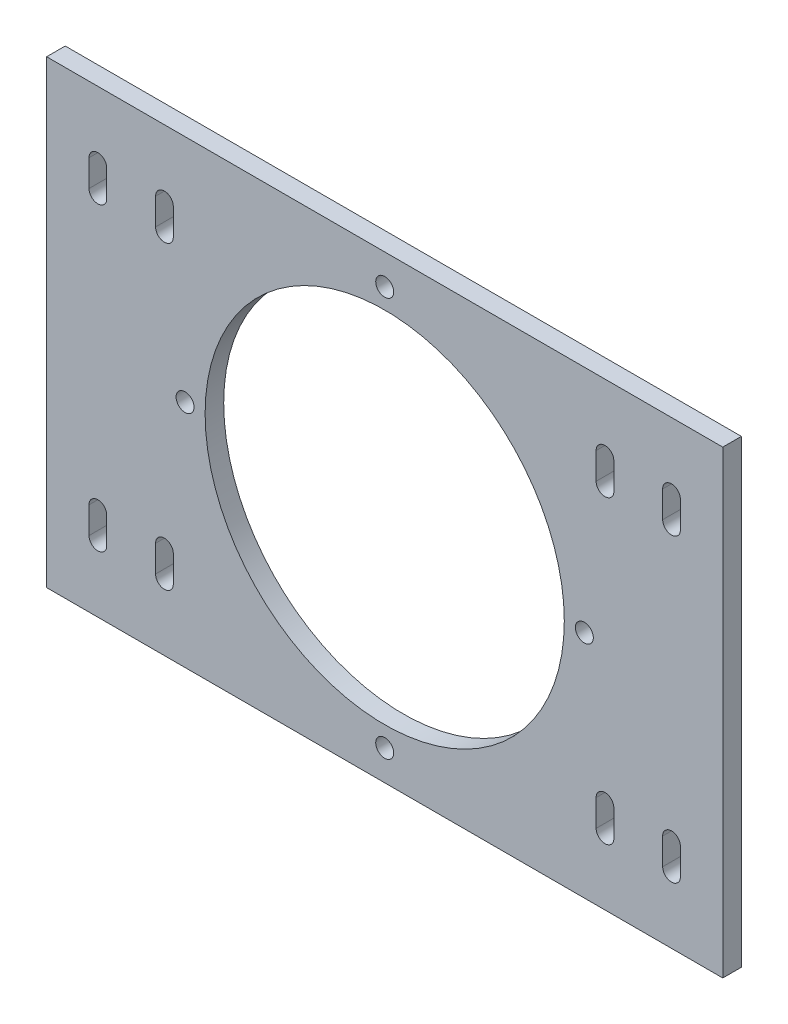
SolidWorks part; units mm, degrees
ref_plane "Front Plane" through (0, 0, 0) normal (0, 0, 1) x (1, 0, 0)
ref_plane "Top Plane" through (0, 0, 0) normal (0, 1, 0) x (1, 0, 0)
ref_plane "Right Plane" through (0, 0, 0) normal (1, 0, 0) x (0, 0, -1)
sketch "Sketch1" plane through (0, 0, 0) normal (0, 0, 1) x (1, 0, 0)
  line L1 (-76.2, -69.088) -> (76.2, -69.088)
  line L2 (-76.2, -69.088) -> (-76.2, 69.088)
  line L3 (-76.2, 69.088) -> (76.2, 69.088)
  line L4 (76.2, -69.088) -> (76.2, 69.088)
  line L5 (-76.2, -69.088) -> (76.2, 69.088) construction
  line L6 (-76.2, 69.088) -> (76.2, -69.088) construction
  circle A1 centre (0, 0) radius 53.975
  point P0 (0, 0)
  dimension "D3" = 107.95
  dimension "D1" = 152.4
  dimension "D2" = 138.176
extrude "Boss-Extrude1" add sketch "Sketch1" along normal blind 5.588
extrude "Cut-Extrude4" cut sketch "Sketch5" against normal through all
sketch "Sketch5" plane through (-338.2002, -104.4906, 5.588) normal (0, 0, 1) x (0.9999, -0.0127, 0)
  circle A1 centre (403.6261, 63.4063) radius 2.665
sketch "Sketch6" plane through (0, 0, 0) normal (0, 0, -1) x (-1, 0, 0)
  line L0 (-66.2, -46.225) -> (-68.088, -46.225) construction
  line L1 (-66.2, -49.1636) -> (-66.2, -46.225) construction
  line L4 (-66.2, -49.1636) -> (-66.2, -41.1636) construction
  line L5 (-68.865, -49.1636) -> (-68.865, -41.1636)
  line L6 (-63.535, -49.1636) -> (-63.535, -41.1636)
  arc A3 (-68.865, -49.1636) -> (-63.535, -49.1636) centre (-66.2, -49.1636) ccw
  arc A4 (-63.535, -41.1636) -> (-68.865, -41.1636) centre (-66.2, -41.1636) ccw
  circle A5 centre (-66.2, -46.225) radius 2.665 construction
  point P4 (-66.2, -45.1636)
  point P10 (-66.2, -45.1636)
  point P11 (-66.2, -45.1636)
  dimension "D1" = 8
extrude "Cut-Extrude5" cut sketch "Sketch6" against normal through all
mirror "Mirror1" about plane through (0, 0, 0) normal (1, 0, 0) of "Cut-Extrude5" second plane through (0, 0, 0) second plane normal (0, 1, 0)
sketch "Sketch7" plane through (76.2, 0, 0) normal (1, 0, 0) x (0, 0, -1)
  line L4 (0, -69.088) -> (0, 69.088)
  line L5 (0, 69.088) -> (-5.588, 69.088)
  line L6 (-5.588, 69.088) -> (-5.588, -69.088)
  line L7 (-5.588, -69.088) -> (0, -69.088)
  line L8 (0, -69.088) -> (0, 69.088)
  line L9 (0, 69.088) -> (-5.588, 69.088)
  line L10 (-5.588, 69.088) -> (-5.588, -69.088)
  line L11 (-5.588, -69.088) -> (0, -69.088)
  dimension "D1" = 0
extrude "Boss-Extrude2" add sketch "Sketch7" along normal blind 25.4
sketch "Sketch8" plane through (0, 0, 0) normal (0, 0, -1) x (-1, 0, 0)
  line L0 (-66.2, 49.1636) -> (-86.2, 49.1636) construction
  line L2 (-76.2, 49.1636) -> (-76.2, -35.8893) construction
  line L3 (-101.6, -69.088) -> (-101.6, 69.088) construction
  line L4 (-63.535, 49.1636) -> (-63.535, 41.1636) construction
  line L5 (-68.865, 41.1636) -> (-68.865, 49.1636) construction
  line L6 (-63.535, 49.1636) -> (-63.535, 41.1636)
  line L7 (-68.865, 41.1636) -> (-68.865, 49.1636)
  line L8 (-83.535, 41.1636) -> (-83.535, 49.1636)
  line L9 (-88.865, 49.1636) -> (-88.865, 41.1636)
  arc A0 (-68.865, 41.1636) -> (-63.535, 41.1636) centre (-66.2, 41.1636) ccw construction
  arc A1 (-63.535, 49.1636) -> (-68.865, 49.1636) centre (-66.2, 49.1636) ccw construction
  arc A2 (-68.865, 41.1636) -> (-63.535, 41.1636) centre (-66.2, 41.1636) ccw
  arc A3 (-63.535, 49.1636) -> (-68.865, 49.1636) centre (-66.2, 49.1636) ccw
  arc A4 (-88.865, 49.1636) -> (-83.535, 49.1636) centre (-86.2, 49.1636) cw
  arc A5 (-83.535, 41.1636) -> (-88.865, 41.1636) centre (-86.2, 41.1636) cw
  point P3 (-87.9561, 49.1636)
  point P7 (-101.6, 49.1636)
  dimension "D1" = 25.4
extrude "Cut-Extrude6" cut sketch "Sketch8" against normal through all
mirror "Mirror2" about plane through (0, 0, 0) normal (0, 1, 0) of "Cut-Extrude6"
mirror "Mirror3" about plane through (0, 0, 0) normal (1, 0, 0) of "Mirror2", "Cut-Extrude6", "Boss-Extrude2"
extrude "Cut-Extrude7" cut sketch "Sketch9" against normal through all
sketch "Sketch9" plane through (-338.2002, -129.8906, 0) normal (0, 0, -1) x (-0.9999, 0.0127, 0)
  circle A4 centre (-276.525, 133.4198) radius 2.7
  circle A5 centre (-337.2836, 74.188) radius 2.7
  circle A6 centre (-396.5153, 134.9466) radius 2.7
  circle A7 centre (-335.7568, 194.1783) radius 2.7
